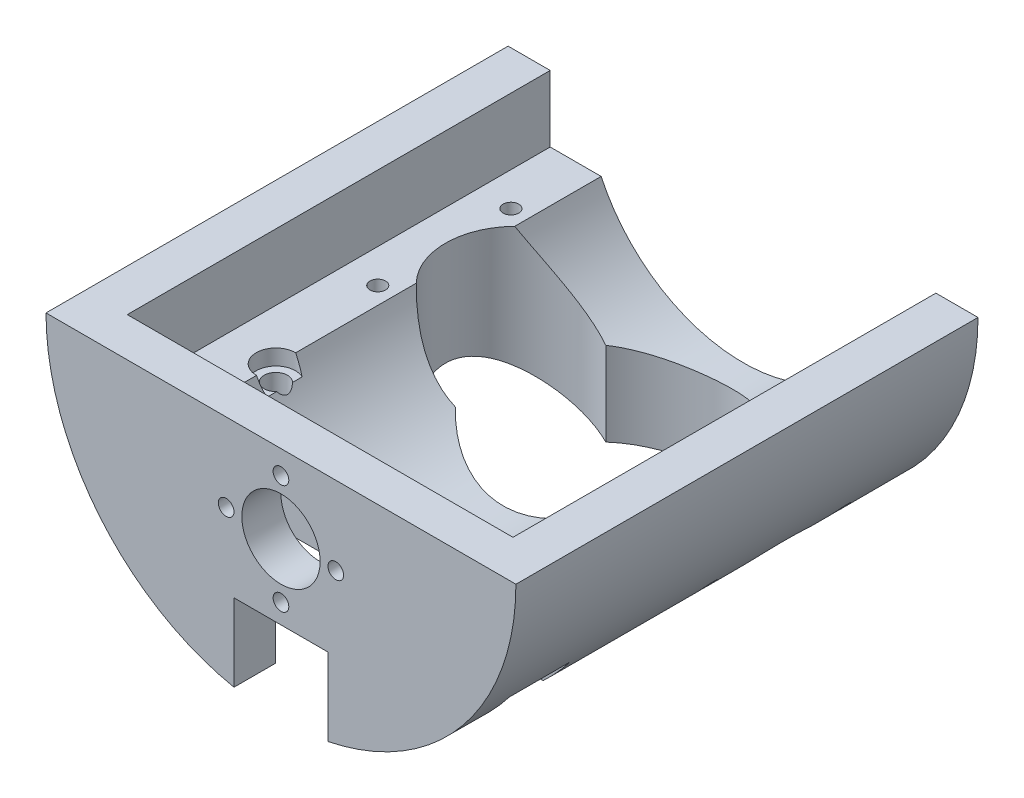
SolidWorks part; units mm, degrees
ref_plane "Front Plane" through (0, 0, 0) normal (0, 0, 1) x (1, 0, 0)
ref_plane "Top Plane" through (0, 0, 0) normal (0, 1, 0) x (1, 0, 0)
ref_plane "Right Plane" through (0, 0, 0) normal (1, 0, 0) x (0, 0, -1)
sketch "Sketch1" plane through (0, 0, 0) normal (0, 1, 0) x (1, 0, 0)
  line L14 (-23.8235, -16.6748) -> (23.8235, -16.6748)
  line L15 (-23.8235, -16.6748) -> (-23.8235, -8.9242)
  line L16 (-23.8235, -8.9242) -> (23.8235, -8.9242)
  line L17 (23.8235, -16.6748) -> (23.8235, -8.9242)
  line L18 (-23.8235, -16.6748) -> (23.8235, -8.9242) construction
  line L19 (-23.8235, -8.9242) -> (23.8235, -16.6748) construction
  circle A0 centre (-20.32, 27.68) radius 1
  circle A1 centre (21.68, 27.68) radius 1
  circle A2 centre (21.68, 10.68) radius 1
  circle A3 centre (-20.32, 10.68) radius 1
  arc A4 (10.6898, 28.1687) -> (12.4855, 10.7596) centre (13.68, 19.68) cw
  arc A6 (12.4855, 10.7596) -> (-10.4855, 10.7596) centre (1, 21.68) cw
  arc A7 (10.6898, 28.1687) -> (-8.6898, 28.1687) centre (1, 21.68) ccw
  arc A8 (-8.6898, 28.1687) -> (-10.4855, 10.7596) centre (-11.68, 19.68) ccw
  circle A9 centre (-18.15, -4.5) radius 1.5
  circle A10 centre (18.15, -4.5) radius 1.5
  point P0 (0, -12.7995)
  dimension "D5" = 2
  dimension "D6" = 2
  dimension "D9" = 9
  dimension "D11" = 17
  dimension "D12" = 0
  dimension "D8" = 9
  dimension "D17" = 25.36
  dimension "D3" = 12.68
  dimension "D10" = 17
  dimension "D13" = 0
  dimension "D14" = 8
  dimension "D15" = 42
  dimension "D16" = 2
  dimension "D22" = 8
sketch "Sketch2" plane through (0, 0, 0) normal (0, 0, 1) x (1, 0, 0)
  circle A0 centre (0, 0) radius 30
  dimension "D1" = 60
extrude "Boss-Extrude1" add sketch "Sketch2" along normal blind 22 and the other way blind 37
extrude "Cut-Extrude2" cut sketch "Sketch1" against normal through all both and the other way through all
sketch "Sketch3" plane through (0, 0, -37) normal (0, 0, -1) x (-1, 0, 0)
  line L0 (-30, 0) -> (30, 0)
  arc A0 (-30, 0) -> (30, 0) centre (0, 0) cw
  circle A1 centre (0, 0) radius 30 construction
extrude "Cut-Extrude3" cut sketch "Sketch3" against normal blind 77
sketch "Sketch4" plane through (0, 0, 0) normal (1, 0, 0) x (0, 0, -1)
  line L1 (-16.6748, -30) -> (3.3252, -30)
  line L2 (-16.6748, -30) -> (-16.6748, -22)
  line L3 (-16.6748, -22) -> (3.3252, -22)
  line L4 (3.3252, -30) -> (3.3252, -22)
  dimension "D1" = 8
  dimension "D2" = 20
extrude "Cut-Extrude4" cut sketch "Sketch4" against normal through all both and the other way through all
sketch "Sketch5" plane through (0, 0, 22) normal (0, 0, -1) x (-1, 0, 0)
  circle A7 centre (0, -10) radius 5
  arc A8 (-30, 0) -> (30, 0) centre (0, 0) ccw construction
  circle A9 centre (-7, -10) radius 1
  circle A10 centre (0, -3) radius 1
  circle A11 centre (7, -10) radius 1
  circle A12 centre (0, -17) radius 1
  point P25 (0, -30)
  point P40 (0, -10)
  dimension "D2" = 10
  dimension "D6" = 2
  dimension "D5" = 20
  dimension "D7" = 7
  dimension "D8" = 4
extrude "Cut-Extrude5" cut sketch "Sketch5" against normal blind 14 and the other way through all
sketch "Sketch7" plane through (0, 0, -37) normal (0, 0, -1) x (-1, 0, 0)
  line L0 (-30, 0) -> (30, 0) construction
  line L1 (-20, 0) -> (20, 0)
  arc A0 (-20, 0) -> (20, 0) centre (0, 0) ccw
  dimension "D1" = 20
extrude "Cut-Extrude7" cut sketch "Sketch7" against normal blind 54
sketch "Sketch8" plane through (0, 0, -37) normal (0, 0, -1) x (-1, 0, 0)
  line L1 (-24.6231, 8.4663) -> (24.6231, 8.4663)
  line L2 (-24.6231, 8.4663) -> (-24.6231, -8.4663)
  line L3 (-24.6231, -8.4663) -> (24.6231, -8.4663)
  line L4 (24.6231, 8.4663) -> (24.6231, -8.4663)
  line L5 (-24.6231, 8.4663) -> (24.6231, -8.4663) construction
  line L6 (-24.6231, -8.4663) -> (24.6231, 8.4663) construction
  point P0 (0, 0)
  dimension "D1" = 49.2463
extrude "Cut-Extrude8" cut sketch "Sketch8" against normal blind 54
sketch "Sketch9" plane through (0, -8.4663, 0) normal (0, 1, 0) x (1, 0, 0)
  circle A0 centre (18.15, -4.5) radius 2.5
  circle A1 centre (-18.15, -4.5) radius 2.5
  dimension "D1" = 5
  dimension "D2" = 5
extrude "Cut-Extrude9" cut sketch "Sketch9" against normal blind 2
sketch "Sketch10" plane through (0, 0, 22) normal (0, 0, 1) x (1, 0, 0)
  line L1 (6, -40.5) -> (-6, -40.5)
  line L2 (6, -40.5) -> (6, -19.5)
  line L3 (6, -19.5) -> (-6, -19.5)
  line L4 (-6, -40.5) -> (-6, -19.5)
  line L5 (6, -40.5) -> (-6, -19.5) construction
  line L6 (6, -19.5) -> (-6, -40.5) construction
  arc A0 (-30, 0) -> (30, 0) centre (0, 0) ccw construction
  point P0 (0, -30)
  dimension "D1" = 21
  dimension "D2" = 12
extrude "Cut-Extrude10" cut sketch "Sketch10" against normal blind 8
sketch "Sketch6" plane through (0, 0, 22) normal (0, 0, -1) x (-1, 0, 0)
  line L0 (-30, 0) -> (-24.6231, 0) construction
  line L1 (-24.9959, 0) -> (24.9959, 0)
  arc A0 (-24.9959, 0) -> (24.9959, 0) centre (0, 0) ccw
